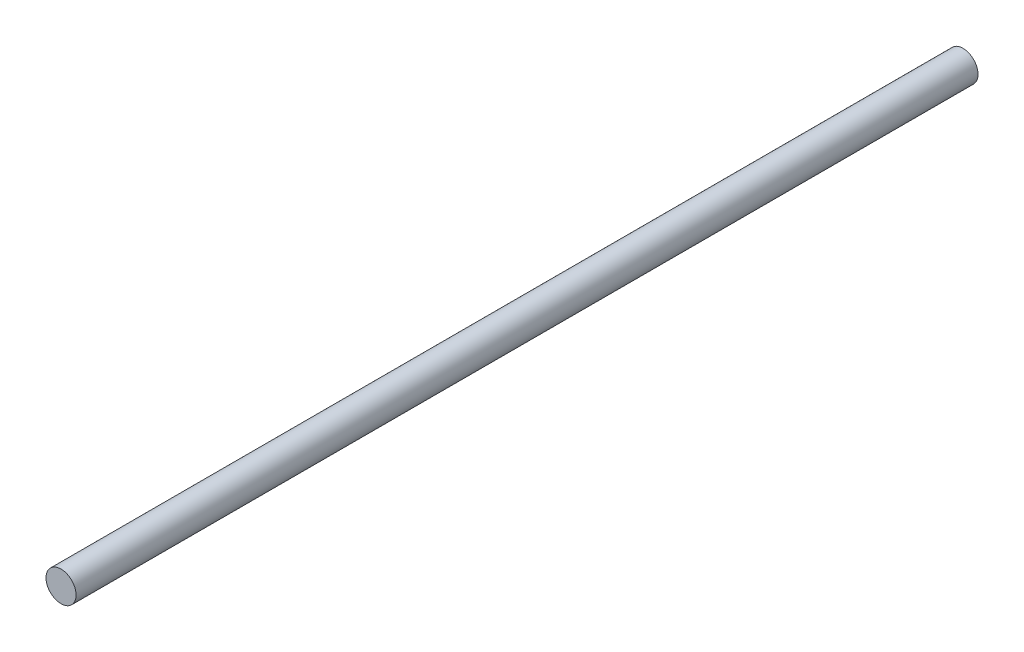
SolidWorks part; units mm, degrees
ref_plane "Front Plane" through (0, 0, 0) normal (0, 0, 1) x (1, 0, 0)
ref_plane "Top Plane" through (0, 0, 0) normal (0, 1, 0) x (1, 0, 0)
ref_plane "Right Plane" through (0, 0, 0) normal (1, 0, 0) x (0, 0, -1)
sketch "Sketch1" plane through (0, 0, 0) normal (0, 0, 1) x (1, 0, 0)
  circle A0 centre (0, 0) radius 1
  dimension "D1" = 2
extrude "Boss-Extrude1" add sketch "Sketch1" along normal blind 45
sketch "Sketch2" plane through (0, 0, 45) normal (0, 0, 1) x (1, 0, 0)
  circle A0 centre (0, 0) radius 1
extrude "Cut-Extrude1" cut sketch "Sketch2" against normal blind 20
sketch "Sketch3" plane through (0, 0, 25) normal (0, 0, 1) x (1, 0, 0)
  circle A0 centre (0, 0) radius 1
extrude "Boss-Extrude2" add sketch "Sketch3" along normal blind 25
sketch "Sketch4" plane through (0, 0, 50) normal (0, 0, 1) x (1, 0, 0)
  circle A0 centre (0, 0) radius 1
extrude "Boss-Extrude3" add sketch "Sketch4" along normal blind 5
sketch "Sketch5" plane through (0, 0, 55) normal (0, 0, 1) x (1, 0, 0)
  circle A0 centre (0, 0) radius 1
extrude "Boss-Extrude4" add sketch "Sketch5" along normal blind 5
